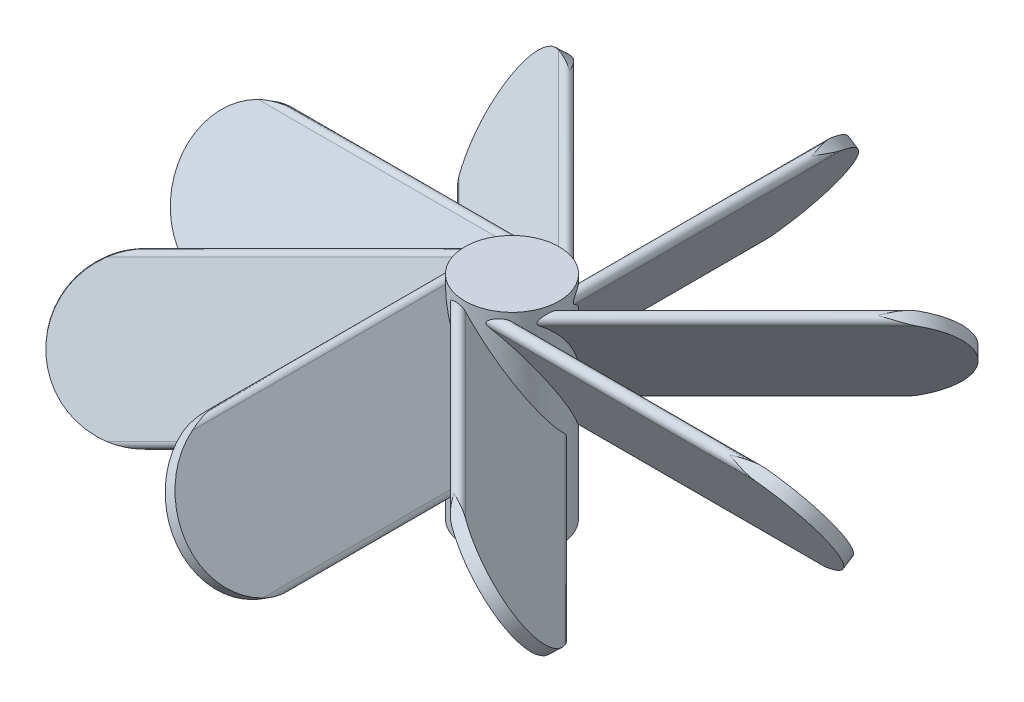
SolidWorks part; units mm, degrees
ref_plane "Front Plane" through (0, 0, 0) normal (0, 0, 1) x (1, 0, 0)
ref_plane "Top Plane" through (0, 0, 0) normal (0, 1, 0) x (1, 0, 0)
ref_plane "Right Plane" through (0, 0, 0) normal (1, 0, 0) x (0, 0, -1)
sketch "Sketch1" plane through (0, 90, 0) normal (0, 1, 0) x (1, 0, 0)
  circle A0 centre (0, -500) radius 20
  dimension "D1" = 40
extrude "Boss-Extrude1" add sketch "Sketch1" along normal blind 90
ref_point "Point1"
ref_plane "Plane1" through (0, 0, 500) normal (0, 0, -1) x (-1, 0, 0)
sketch "Sketch2" plane through (0, 0, 500) normal (0, 0, -1) x (-1, 0, 0)
  line L0 (-16.0655, 174.9459) -> (13.8906, 128.3476) construction
  line L1 (-13.9856, 176.283) -> (15.9705, 129.6846)
  line L2 (-18.1454, 173.6089) -> (11.8107, 127.0105)
  arc A0 (-13.9856, 176.283) -> (-18.1454, 173.6089) centre (-16.0655, 174.9459) ccw
  arc A1 (11.8107, 127.0105) -> (15.9705, 129.6846) centre (13.8906, 128.3476) ccw
  point P2 (-1.0874, 151.6467)
extrude "Boss-Extrude2" add sketch "Sketch2" along normal blind 140
sketch "Sketch3" plane through (-70.2905, 45.1868, 0) normal (-0.8412, 0.5408, 0) x (0, 0, 1)
  line L0 (490.1434, 158.3208) -> (360, 158.3208) construction
  line L1 (360, 97.9792) -> (487.0339, 97.9792) construction
  line L2 (360, 100.4518) -> (360, 155.8483) construction
  line L3 (390.1708, 158.3208) -> (379.5152, 182.5343)
  line L4 (379.5152, 182.5343) -> (295.5483, 135.8512)
  line L5 (295.5483, 135.8512) -> (337.5317, 72.876)
  line L6 (337.5317, 72.876) -> (390.1708, 97.9792)
  arc A0 (390.1708, 158.3208) -> (390.1708, 97.9792) centre (390.1708, 128.15) ccw
extrude "Cut-Extrude1" cut sketch "Sketch3" against normal blind 10
pattern_circular "CirPattern1" count 8 over 360 about axis through (0, 0, 500) along (0, 1, 0) of "Boss-Extrude2", "Cut-Extrude1"
